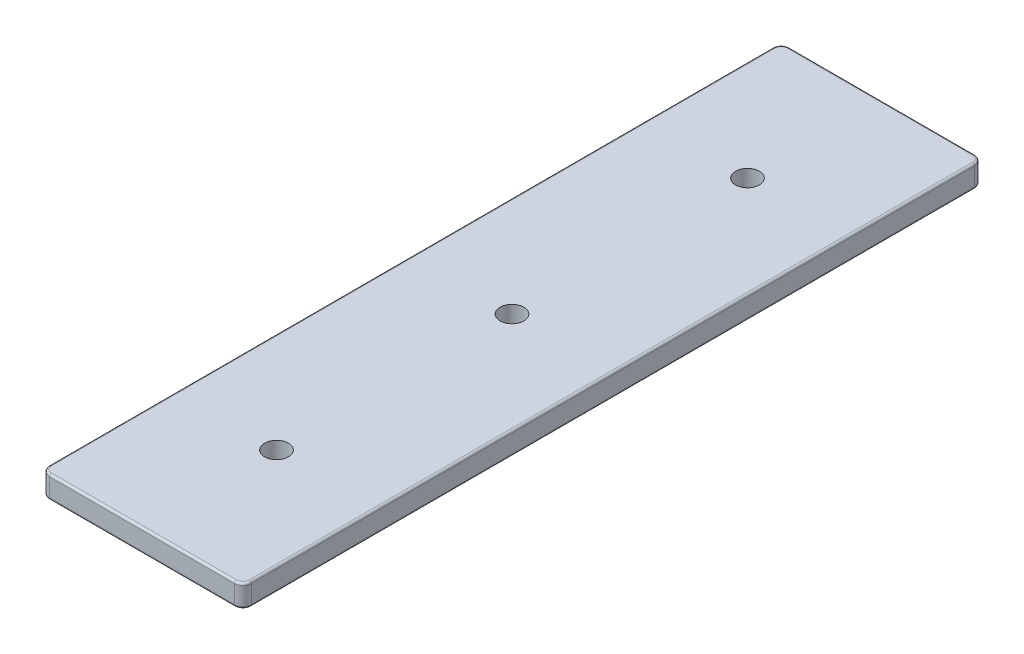
SolidWorks part; units mm, degrees
ref_plane "Front Plane" through (0, 0, 0) normal (0, 0, 1) x (1, 0, 0)
ref_plane "Top Plane" through (0, 0, 0) normal (0, 1, 0) x (1, 0, 0)
ref_plane "Right Plane" through (0, 0, 0) normal (1, 0, 0) x (0, 0, -1)
sketch "Sketch1" plane through (0, 0, 0) normal (0, 0, 1) x (1, 0, 0)
  line L0 (-19.05, 0) -> (19.05, 0)
  line L1 (-19.05, 0) -> (-19.05, 12.7)
  line L2 (-19.05, 12.7) -> (-11.5288, 12.7)
  line L3 (-11.5288, 12.7) -> (-14.8167, 4.7625)
  line L4 (0, 0) -> (0, 4.7625) construction
  line L5 (-14.8167, 4.7625) -> (14.8167, 4.7625)
  line L6 (11.5288, 12.7) -> (14.8167, 4.7625)
  line L7 (19.05, 0) -> (19.05, 12.7)
  line L8 (19.05, 12.7) -> (11.5288, 12.7)
  point P4 (0, 0)
  dimension "D1" = 67.5
  dimension "D2" = 4.7625
  dimension "D3" = 12.7
  dimension "D4" = 19.05
  dimension "D5" = 4.2333
extrude "Boss-Extrude1" add sketch "Sketch1" along normal blind 139.7
fillet "Fillet1" radius 1.27 6 edges at (19.05, 12.7, 69.85) (11.5288, 12.7, 69.85) (-19.05, 12.7, 69.85) (-11.5288, 12.7, 69.85) (14.8167, 4.7625, 69.85) (-14.8167, 4.7625, 69.85)
sketch "Sketch2" plane through (0, 0, 139.7) normal (0, 0, 1) x (1, 0, 0)
  line L3 (-11.9042, 10.7982) -> (11.9042, 10.7982)
  line L6 (11.9042, 10.7982) -> (13.7373, 6.3727)
  line L7 (12.916, 5.1435) -> (-12.916, 5.1435)
  line L8 (-13.7373, 6.3727) -> (-11.9042, 10.7982)
  line L9 (11.9042, 10.7982) -> (13.7373, 6.3727)
  line L10 (12.916, 5.1435) -> (-12.916, 5.1435)
  line L11 (-13.7373, 6.3727) -> (-11.9042, 10.7982)
  arc A4 (12.916, 5.1435) -> (13.7373, 6.3727) centre (12.916, 6.0325) ccw
  arc A5 (-13.7373, 6.3727) -> (-12.916, 5.1435) centre (-12.916, 6.0325) ccw
  arc A6 (12.916, 5.1435) -> (13.7373, 6.3727) centre (12.916, 6.0325) ccw
  arc A7 (-13.7373, 6.3727) -> (-12.916, 5.1435) centre (-12.916, 6.0325) ccw
  dimension "D1" = 0.381
extrude "Boss-Extrude2" add sketch "Sketch2" along normal blind 25.4 separate body
fillet "Fillet2" radius 1.27 2 edges at (11.9042, 10.7982, 152.4) (-11.9042, 10.7982, 152.4)
fillet "Fillet3" radius 1.27 28 edges at (12.3736, 12.1356, 0) (13.1728, 8.7313, 0) (13.9719, 5.3269, 0) (0, 4.7625, 0) (-13.9719, 5.3269, 0) (-13.1728, 8.7313, 0) (-12.3736, 12.1356, 0) (-15.6048, 12.7, 0) (-18.678, 12.328, 0) (-19.05, 5.715, 0) (0, 0, 0) (19.05, 5.715, 0) (18.678, 12.328, 0) (15.6048, 12.7, 0) (0, 0, 139.7) (-19.05, 5.715, 139.7) (-18.678, 12.328, 139.7) (-15.6048, 12.7, 139.7) (-12.3736, 12.1356, 139.7) (-13.1728, 8.7313, 139.7) (-13.9719, 5.3269, 139.7) (0, 4.7625, 139.7) (13.9719, 5.3269, 139.7) (13.1728, 8.7313, 139.7) (12.3736, 12.1356, 139.7) (15.6048, 12.7, 139.7) (18.678, 12.328, 139.7) (19.05, 5.715, 139.7)
fillet "Fillet4" radius 1.27 16 edges at (-11.7612, 10.5842, 139.7) (-12.9831, 8.1935, 139.7) (-13.6552, 5.5386, 139.7) (0, 5.1435, 139.7) (13.6552, 5.5386, 139.7) (12.9831, 8.1935, 139.7) (11.7612, 10.5842, 139.7) (0, 10.7982, 139.7) (13.6552, 5.5386, 165.1) (0, 5.1435, 165.1) (-13.6552, 5.5386, 165.1) (-12.9831, 8.1935, 165.1) (-11.7612, 10.5842, 165.1) (0, 10.7982, 165.1) (11.7612, 10.5842, 165.1) (12.9831, 8.1935, 165.1)
sketch "Sketch3" plane through (0, 5.1435, 0) normal (0, -1, 0) x (1, 0, 0)
  line L0 (-12.916, 152.4) -> (12.916, 152.4) construction
  line L1 (-12.916, 163.83) -> (-12.916, 140.97) construction
  line L2 (12.916, 163.83) -> (12.916, 140.97) construction
  line L3 (0, 163.83) -> (0, 140.97) construction
  line L4 (12.916, 163.83) -> (-12.916, 163.83) construction
  line L5 (-12.916, 140.97) -> (12.916, 140.97) construction
  point P12 (0, 152.4)
hole_wizard "CSK for 1/4 Flat Head Machine Screw (100)1" positions "3DSketch1" profile "Sketch4" countersink size "1/4" standard "ANSI Inch"
sketch3d "3DSketch1"
  point P0 (0, 5.1435, 152.4)
sketch "Sketch4" plane through (0, 5.1435, 152.4) normal (1, 0, 0) x (0, 0, -1)
  line L0 (0, 0) -> (0, 7.5565)
  line L1 (0, 7.5565) -> (3.3782, 7.5565)
  line L2 (3.3782, 7.5565) -> (3.3782, 2.5682)
  line L3 (3.3782, 2.5682) -> (6.4389, 0)
  line L5 (6.4389, 0) -> (0, 0)
  line L6 (-3.3782, 2.5682) -> (-6.4389, 0) construction
  line L11 (0, -6.35) -> (0, 107.95) construction
  dimension "Thru Hole Dia." = 6.7564
  dimension "Thru Hole Depth" = 7.5565
  dimension "Near C'Sink Dia." = 12.8778
  dimension "Near C'Sink Angle" = 100
ref_plane "Plane2" through (0, -0.3969, 0) normal (0, -1, 0) x (-1, 0, 0)
sketch "Sketch9" plane through (0, -0.3969, 0) normal (0, -1, 0) x (-1, 0, 0)
  line L0 (-19.05, -138.43) -> (-19.05, -1.27) construction
  line L1 (19.05, -139.7) -> (-19.05, -139.7)
  line L2 (19.05, -139.7) -> (19.05, 0)
  line L3 (19.05, 0) -> (-19.05, 0)
  line L4 (-19.05, -139.7) -> (-19.05, 0)
  line L5 (19.05, -139.7) -> (-19.05, 0) construction
  line L6 (19.05, 0) -> (-19.05, -139.7) construction
  line L7 (19.05, -138.43) -> (19.05, -1.27) construction
  line L8 (-17.78, 0) -> (17.78, 0) construction
  line L9 (17.78, -139.7) -> (-17.78, -139.7) construction
  point P0 (0, -69.85)
extrude "Boss-Extrude3" add sketch "Sketch9" along normal blind 4.2333 separate body
fillet "Fillet6" radius 1.5875 4 edges at (19.05, -2.5135, 139.7) (-19.05, -2.5135, 139.7) (-19.05, -2.5135, 0) (19.05, -2.5135, 0)
fillet "Fillet7" radius 0.3969 16 edges at (18.585, -0.3969, 0.465) (0, -0.3969, 0) (-18.585, -0.3969, 0.465) (-19.05, -0.3969, 69.85) (-18.585, -0.3969, 139.235) (0, -0.3969, 139.7) (18.585, -0.3969, 139.235) (18.585, -4.6302, 0.465) (0, -4.6302, 0) (-18.585, -4.6302, 0.465) (-19.05, -4.6302, 69.85) (-18.585, -4.6302, 139.235) (0, -4.6302, 139.7) (18.585, -4.6302, 139.235) (19.05, -0.3969, 69.85) (19.05, -4.6302, 69.85)
delete or keep bodies "Body-Delete/Keep 1" type delete bodies bodies 103
sketch "Sketch5" plane through (0, 4.7625, 0) normal (0, 1, 0) x (1, 0, 0)
  line L0 (0, -1.27) -> (0, -138.43) construction
  line L1 (12.916, -1.27) -> (-12.916, -1.27) construction
  line L2 (-12.916, -138.43) -> (12.916, -138.43) construction
  point P6 (0, -69.85)
hole_wizard "CSK for #8 Flat Head Machine Screw (100)1" positions "3DSketch2" profile "Sketch6" countersink size "#8" standard "ANSI Inch"
sketch3d "3DSketch2"
  point P0 (0, 4.7625, 69.85)
sketch "Sketch6" plane through (0, 4.7625, 69.85) normal (1, 0, 0) x (0, 0, 1)
  line L0 (0, 0) -> (0, 9.3927)
  line L1 (0, 9.3927) -> (2.2479, 9.3927)
  line L2 (2.2479, 9.3927) -> (2.2479, 1.6518)
  line L3 (2.2479, 1.6518) -> (4.2164, 0)
  line L5 (4.2164, 0) -> (0, 0)
  line L6 (-2.2479, 1.6518) -> (-4.2164, 0) construction
  line L11 (0, -6.35) -> (0, 107.95) construction
  dimension "Thru Hole Dia." = 4.4958
  dimension "Thru Hole Depth" = 9.3927
  dimension "Near C'Sink Dia." = 8.4328
  dimension "Near C'Sink Angle" = 100
pattern_linear "LPattern1" count 2 spacing 44.45 along (0, 0, 1) count 2 spacing 44.45 along (0, 0, -1) of "CSK for #8 Flat Head Machine Screw (100)1"
fillet "Fillet5" radius 1.5875 3 edges at (0, 4.7625, 29.6164) (0, 4.7625, 74.0664) (0, 4.7625, 118.5164)
delete or keep bodies "Body-Delete/Keep 2" type delete bodies bodies 105
